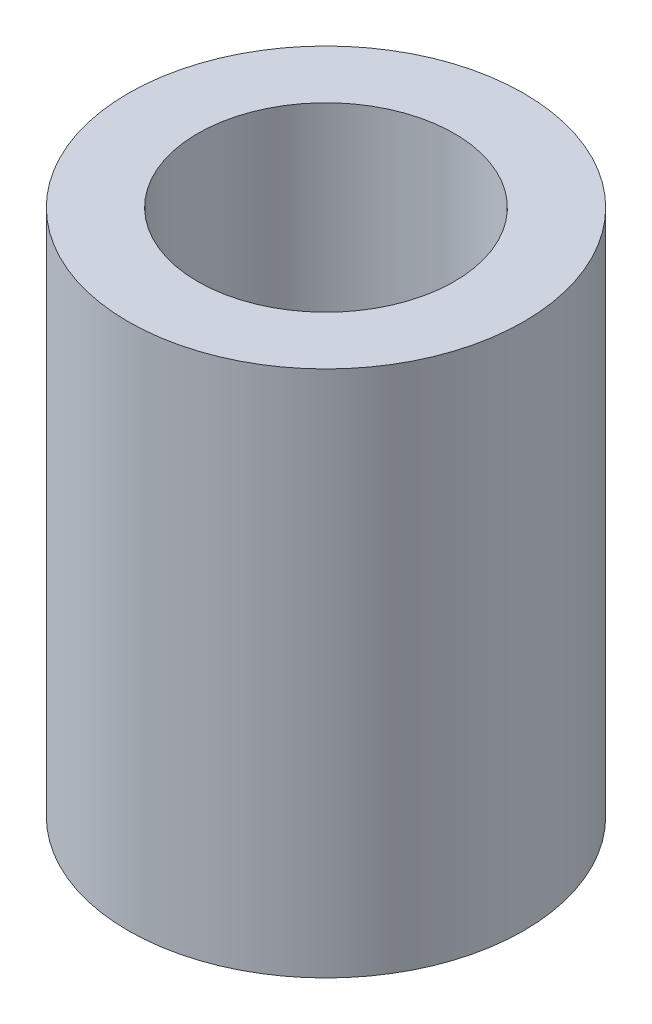
SolidWorks part; units mm, degrees
ref_plane "Front Plane" through (0, 0, 0) normal (0, 0, 1) x (1, 0, 0)
ref_plane "Top Plane" through (0, 0, 0) normal (0, 1, 0) x (1, 0, 0)
ref_plane "Right Plane" through (0, 0, 0) normal (1, 0, 0) x (0, 0, -1)
sketch "Sketch1" plane through (0, 0, 0) normal (0, 1, 0) x (1, 0, 0)
  circle A0 centre (0, 0) radius 7.7083
  circle A1 centre (0, 0) radius 5
  dimension "D1" = 15.4167
  dimension "D2" = 10
extrude "Boss-Extrude3" add sketch "Sketch1" along normal mid plane 20.5556
equation "\"D1@Sketch1\"=(\"Upper_Mount_largest_radius\"/0.8)/1.5"
equation "\"D1\"= \"SHOCK_MOUNT_BUSHING_DIA\" / 0.4375"
equation "\"D1@Boss-Extrude3\"=((\"Upper_Mount_largest_radius\"/1.2)/1.5)*2"
equation "\"Upper_Mount_largest_radius\" =18.5"
equation "\"Upper_mount_wall_thickness\" =12"
equation "\"Lower_Mount_piston_rod_length\" =149"
equation "\"Lower_Mount_piston_rod_radius\"\t=4.9101"
equation "\"Piston_orifice_dia\"=0.47773"
equation "\"Spring_inner_dia\" =80"
equation "\"Spring_wire_dia\" =8"
